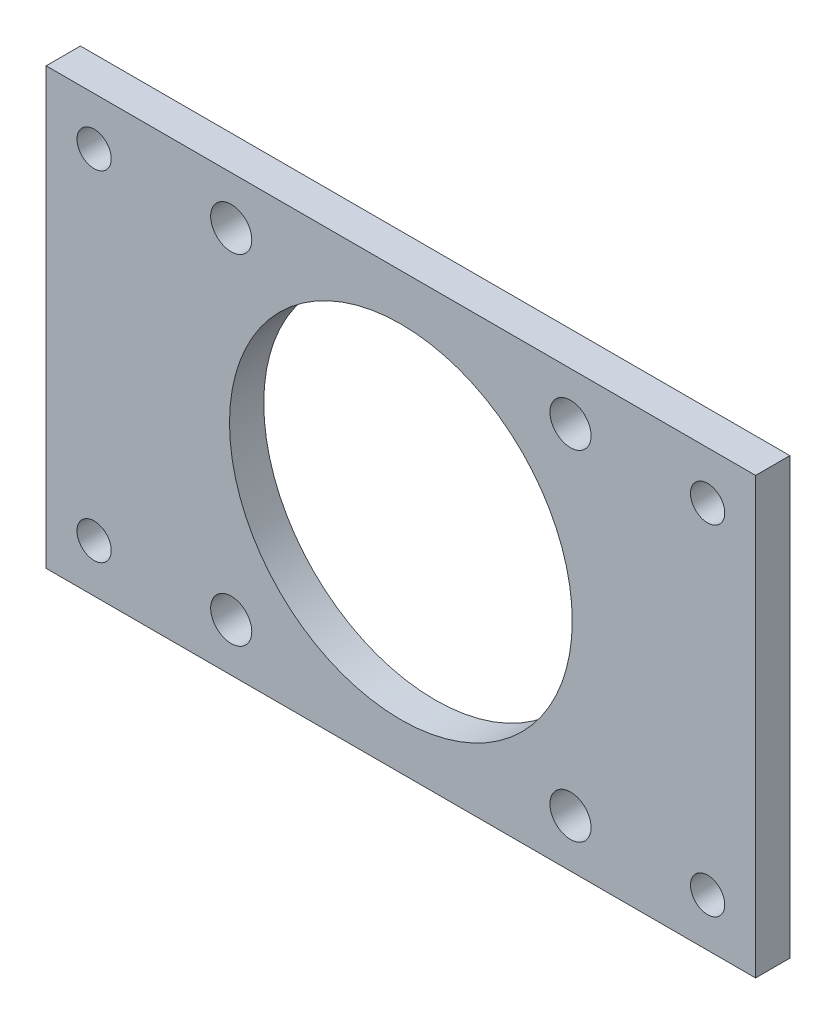
SolidWorks part; units mm, degrees
ref_plane "Front Plane" through (0, 0, 0) normal (0, 0, 1) x (1, 0, 0)
ref_plane "Top Plane" through (0, 0, 0) normal (0, 1, 0) x (1, 0, 0)
ref_plane "Right Plane" through (0, 0, 0) normal (1, 0, 0) x (0, 0, -1)
sketch "Sketch1" plane through (0, 0, 0) normal (0, 0, 1) x (1, 0, 0)
  line L0 (0, 0) -> (96.2706, 96.2706) construction
  line L1 (-1.5465, 0) -> (0, 0) construction
  line L2 (0, 0) -> (166.5092, 0) construction
  line L3 (0, 0) -> (0, 77.8226) construction
  line L5 (-51.7487, 31.7487) -> (51.7487, 31.7487)
  line L6 (-51.7487, 31.7487) -> (-51.7487, -31.7487)
  line L7 (-51.7487, -31.7487) -> (51.7487, -31.7487)
  line L8 (51.7487, 31.7487) -> (51.7487, -31.7487)
  circle A0 centre (0, 0) radius 25
  circle A1 centre (24.7487, 24.7487) radius 3
  circle A2 centre (24.7487, -24.7487) radius 3
  circle A3 centre (-24.7487, -24.7487) radius 3
  circle A4 centre (-24.7487, 24.7487) radius 3
  circle A5 centre (44.7487, 24.7487) radius 2.5
  circle A6 centre (44.7487, -24.7487) radius 2.5
  circle A7 centre (-44.7487, -24.7487) radius 2.5
  circle A8 centre (-44.7487, 24.7487) radius 2.5
  point P17 (0, 0)
  dimension "D2" = 50
  dimension "D4" = 6
  dimension "D6" = 5
  dimension "D1" = 45
  dimension "D3" = 35
  dimension "D7" = 20
  dimension "D8" = 7
  dimension "D9" = 7
  dimension "D10" = 7
  dimension "D11" = 7
  dimension "D5" = 4
extrude "Boss-Extrude1" add sketch "Sketch1" along normal blind 5
